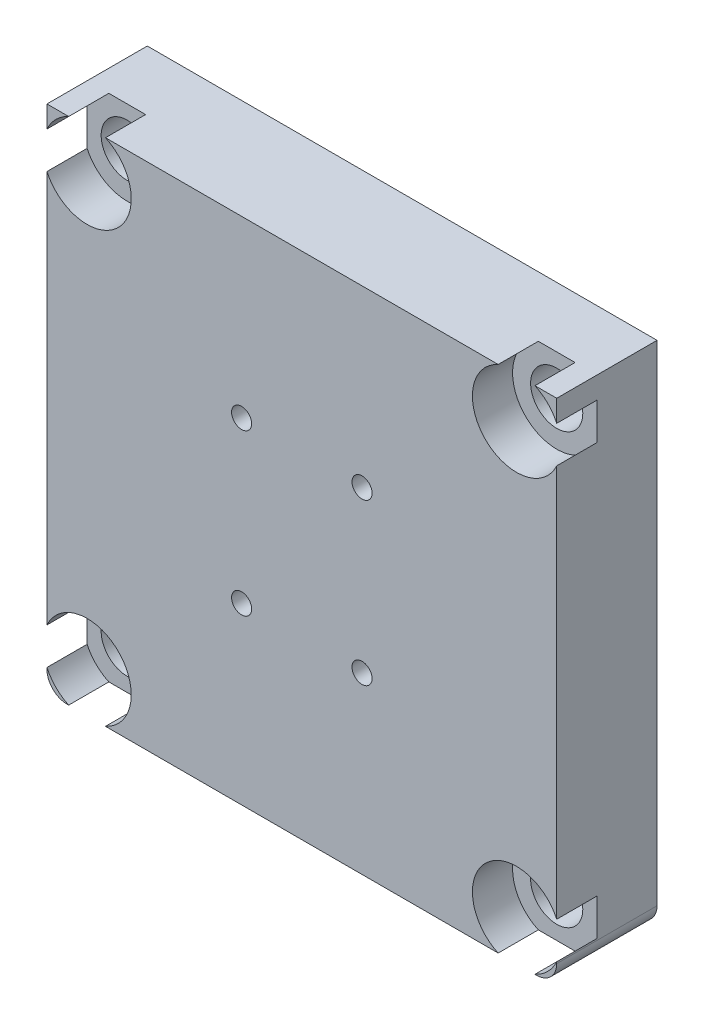
SolidWorks part; units mm, degrees
ref_plane "Front Plane" through (0, 0, 0) normal (0, 0, 1) x (1, 0, 0)
ref_plane "Top Plane" through (0, 0, 0) normal (0, 1, 0) x (1, 0, 0)
ref_plane "Right Plane" through (0, 0, 0) normal (1, 0, 0) x (0, 0, -1)
sketch "Sketch1" plane through (0, 0, 0) normal (0, 0, 1) x (1, 0, 0)
  line L8 (-12.7, 12.7) -> (-12.7, -11.7)
  line L9 (-11.7, -12.7) -> (11.7, -12.7)
  line L10 (12.7, -11.7) -> (12.7, 12.7)
  line L11 (12.7, 12.7) -> (-12.7, 12.7)
  line L12 (-12.7, 12.7) -> (-12.7, -11.7)
  line L13 (-11.7, -12.7) -> (11.7, -12.7)
  line L14 (12.7, -11.7) -> (12.7, 12.7)
  line L15 (12.7, 12.7) -> (-12.7, 12.7)
  arc A4 (-12.7, -11.7) -> (-11.7, -12.7) centre (-11.7, -11.7) ccw
  arc A5 (11.7, -12.7) -> (12.7, -11.7) centre (11.7, -11.7) ccw
  arc A6 (-12.7, -11.7) -> (-11.7, -12.7) centre (-11.7, -11.7) ccw
  arc A7 (11.7, -12.7) -> (12.7, -11.7) centre (11.7, -11.7) ccw
  dimension "D1" = 0
extrude "Boss-Extrude1" add sketch "Sketch1" along normal blind 5
sketch "Sketch2" plane through (0, 0, 5) normal (0, 0, 1) x (1, 0, 0)
  line L1 (-3, 4) -> (3, 4)
  line L2 (-3, 4) -> (-3, -4)
  line L3 (-3, -4) -> (3, -4)
  line L4 (3, 4) -> (3, -4)
  line L5 (-3, 4) -> (3, -4) construction
  line L6 (-3, -4) -> (3, 4) construction
  point P0 (0, 0)
  dimension "D1" = 6
  dimension "D2" = 8
  dimension "D3" = 0
hole_wizard "Ø1.0mm Dowel Hole1" positions "Sketch3" profile "Sketch4" hole size "Ø1.0" standard "ANSI Metric" end condition through all
sketch "Sketch3" plane through (0, 0, 5) normal (0, 0, 1) x (1, 0, 0)
  point P0 (3, -4)
  point P3 (-3, -4)
  point P6 (-3, 4)
  point P9 (3, 4)
sketch "Sketch4" plane through (3, -4, 5) normal (1, 0, 0) x (0, -1, 0)
  line L0 (0, 0) -> (0, 5)
  line L1 (0, 5) -> (0.5, 5)
  line L2 (0.5, 5) -> (0.5, 0)
  line L5 (0.5, 0) -> (0, 0)
  line L11 (0, -6.35) -> (0, 107.95) construction
  dimension "Thru Hole Dia." = 1
  dimension "Thru Hole Depth" = 5
hole_wizard "CBORE for M2 SHCS1" positions "Sketch5" profile "Sketch6" counterbore size "M2" standard "ANSI Metric" end condition through all
sketch "Sketch5" plane through (0, 0, 5) normal (0, 0, 1) x (1, 0, 0)
  point P0 (10.7, -10.7)
  point P3 (-10.7, -10.7)
  point P6 (-10.7, 10.7)
  point P9 (10.7, 10.7)
sketch "Sketch6" plane through (10.7, -10.7, 5) normal (1, 0, 0) x (0, -1, 0)
  line L0 (0, 0) -> (0, 5)
  line L1 (0, 5) -> (1.3, 5)
  line L3 (1.3, 5) -> (1.3, 2)
  line L4 (1.3, 2) -> (2.2, 2)
  line L5 (2.2, 2) -> (2.2, 0)
  line L7 (2.2, 0) -> (0, 0)
  line L11 (0, -6.35) -> (0, 107.95) construction
  dimension "Thru Hole Dia." = 2.6
  dimension "Thru Hole Depth" = 5
  dimension "C'Bore Dia." = 4.4
  dimension "C'Bore Depth" = 2
